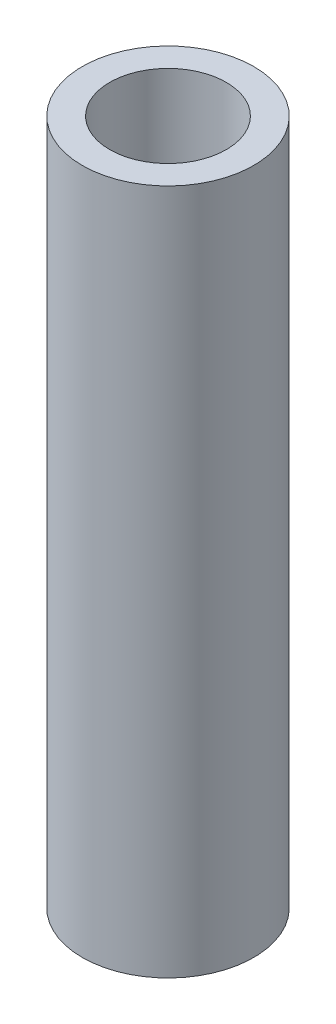
SolidWorks part; units mm, degrees
ref_plane "Front Plane" through (0, 0, 0) normal (0, 0, 1) x (1, 0, 0)
ref_plane "Top Plane" through (0, 0, 0) normal (0, 1, 0) x (1, 0, 0)
ref_plane "Right Plane" through (0, 0, 0) normal (1, 0, 0) x (0, 0, -1)
sketch "Sketch1" plane through (0, 0, 0) normal (0, 1, 0) x (1, 0, 0)
  circle A0 centre (0, 0) radius 2.5
  dimension "D1" = 5
extrude "Boss-Extrude1" add sketch "Sketch1" along normal blind 20
hole_wizard "M3 Clearance Hole1" positions "3DSketch1" profile "Sketch2" hole size "M3" standard "ISO" end condition up to next
sketch3d "3DSketch1"
  line L0 (0, 20, 0) -> (0, 0, 0) construction
  point P0 (0, 20, 0)
sketch "Sketch2" plane through (0, 20, 0) normal (1, 0, 0) x (0, 0, 1)
  line L0 (0, 0) -> (0, 20)
  line L1 (0, 20) -> (1.7, 20)
  line L2 (1.7, 20) -> (1.7, 0)
  line L5 (1.7, 0) -> (0, 0)
  line L11 (0, -6.35) -> (0, 107.95) construction
  dimension "Thru Hole Dia." = 3.4
  dimension "Thru Hole Depth" = 20
